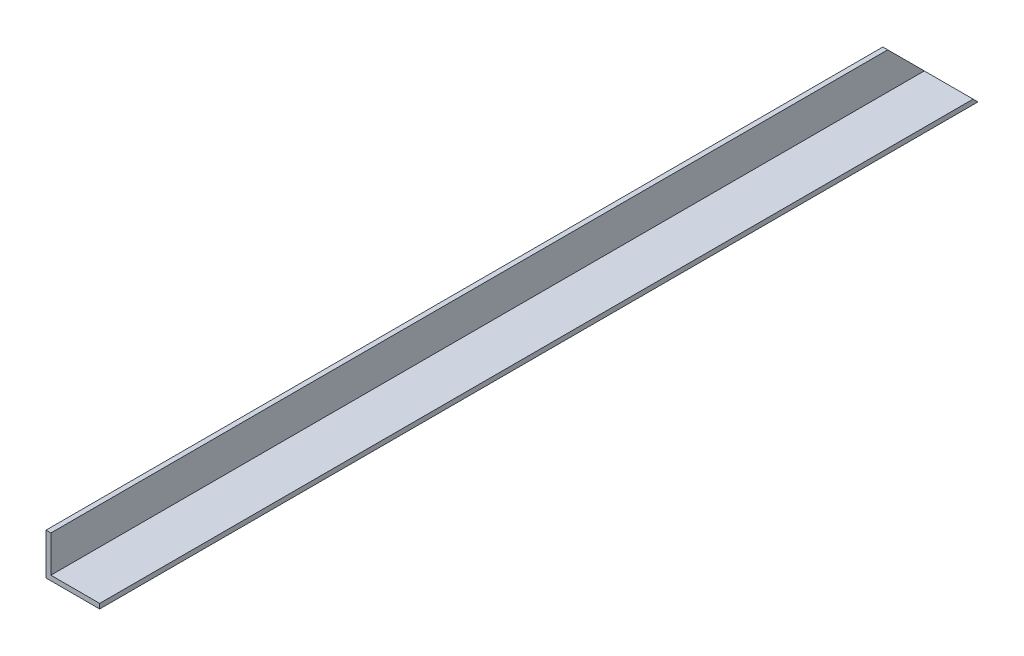
SolidWorks part; units mm, degrees
ref_plane "Front Plane" through (0, 0, 0) normal (0, 0, 1) x (1, 0, 0)
ref_plane "Top Plane" through (0, 0, 0) normal (0, 1, 0) x (1, 0, 0)
ref_plane "Right Plane" through (0, 0, 0) normal (1, 0, 0) x (0, 0, -1)
sketch "Sketch2" plane through (0, 0, 0) normal (0, 0, 1) x (1, 0, 0)
  line L0 (0, 0) -> (0, 17)
  line L1 (0, 17) -> (2, 17)
  line L2 (2, 17) -> (2, 2)
  line L3 (2, 2) -> (22, 2)
  line L4 (22, 2) -> (22, 0)
  line L5 (22, 0) -> (0, 0)
  dimension "D1" = 17
  dimension "D2" = 22
  dimension "D3" = 2
  dimension "D4" = 2
extrude "Boss-Extrude1" add sketch "Sketch2" along normal blind 360
sketch "Sketch3" plane through (0, 0, 0) normal (-1, 0, 0) x (0, 0, 1)
  line L0 (0, 0) -> (17, 17)
  line L1 (360, 17) -> (0, 17) construction
  line L2 (17, 17) -> (0, 17)
  line L3 (0, 17) -> (0, 0)
  dimension "D1" = 45
extrude "Cut-Extrude1" cut sketch "Sketch3" against normal blind 360
